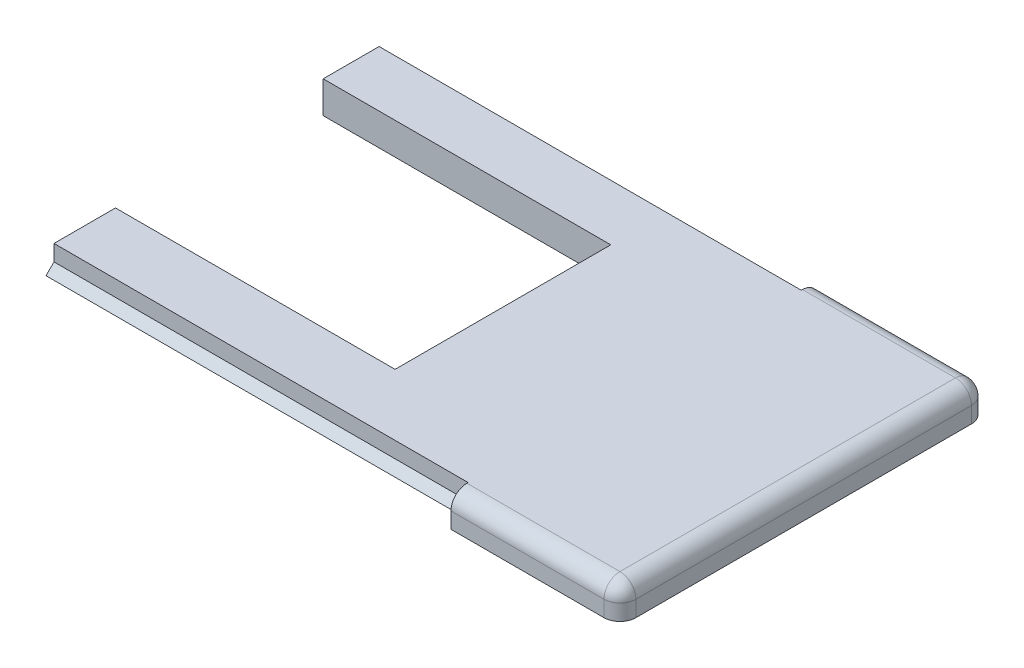
SolidWorks part; units mm, degrees
ref_plane "前视基准面" through (0, 0, 0) normal (0, 0, 1) x (1, 0, 0)
ref_plane "上视基准面" through (0, 0, 0) normal (0, 1, 0) x (1, 0, 0)
ref_plane "右视基准面" through (0, 0, 0) normal (1, 0, 0) x (0, 0, -1)
sketch "草图1" plane through (0, 0, 0) normal (0, 1, 0) x (1, 0, 0)
  line L0 (-35, -21) -> (35, -21)
  line L1 (-35, -21) -> (-35, 21)
  line L2 (-35, 21) -> (35, 21)
  line L3 (35, -21) -> (35, 21)
  line L4 (-35, -21) -> (35, 21) construction
  line L5 (-35, 21) -> (35, -21) construction
  line L10 (35, -21) -> (31, -21)
  line L11 (35, -21) -> (35, -18)
  line L14 (35, 21) -> (31, 21)
  line L15 (35, 21) -> (35, 18)
  line L18 (-35, -21) -> (-23, -21)
  line L19 (-35, -21) -> (-35, -18)
  line L22 (-37, -23) -> (37, -23)
  line L23 (-37, -23) -> (-37, 23)
  line L24 (-37, 23) -> (37, 23)
  line L25 (37, -23) -> (37, 23)
  line L26 (-37, -23) -> (37, 23) construction
  line L27 (-37, 23) -> (37, -23) construction
  line L28 (-34.85, -20.85) -> (-34.85, 20.85)
  line L29 (37, 23) -> (17, 23)
  line L30 (37, 23) -> (37, -23)
  line L31 (37, -23) -> (17, -23)
  line L32 (17, 23) -> (17, -23)
  line L33 (-35, -21) -> (17, -21)
  line L34 (-35, -21) -> (-35, 21)
  line L35 (-35, 21) -> (17, 21)
  line L36 (17, -21) -> (17, 21)
  line L37 (-34.85, 20.85) -> (16.85, 20.85)
  line L39 (-34.85, -20.85) -> (16.85, -20.85)
  line L40 (16.85, 20.85) -> (17, 20.85)
  line L41 (16.85, -20.85) -> (17, -20.85)
  line L43 (16.85, -20.85) -> (16.85, 20.85) construction
  point P0 (0, 0)
  point P21 (0, 0)
  dimension "D1" = 46
  dimension "D2" = 74
  dimension "D3" = 42
  dimension "D4" = 70
  dimension "D5" = 46
  dimension "D6" = 20
  dimension "D7" = 0.15
extrude "凸台-拉伸2" add sketch "草图1" along normal blind 4 contours L39 L41 L36 L40 L37 L28 | L2 L32 L36 L0 L3 | L24 L32 L2 L3 L0 L22 L25
sketch "草图3" plane through (17, 0, 0) normal (-1, 0, 0) x (0, 0, 1)
  line L0 (20.85, 2) -> (21.85, 1)
  line L1 (20.85, 4) -> (20.85, 0) construction
  line L2 (21.85, 1) -> (20.85, 0)
  line L3 (20.85, 4) -> (20.85, 0) construction
  line L4 (20.85, 0) -> (20.85, 2)
  line L5 (20.85, 0) -> (23, 0) construction
  dimension "D1" = 45
  dimension "D2" = 45
  dimension "D3" = 1
sketch "草图4" plane through (17, 0, 0) normal (-1, 0, 0) x (0, 0, 1)
  line L0 (-20.85, 2) -> (-21.85, 1)
  line L1 (-20.85, 4) -> (-20.85, 0) construction
  line L2 (-21.85, 1) -> (-20.85, 0)
  line L3 (-20.85, 4) -> (-20.85, 0) construction
  line L4 (-20.85, 0) -> (-20.85, 2)
  line L5 (-23, 0) -> (-20.85, 0) construction
  dimension "D1" = 45
  dimension "D2" = 45
  dimension "D3" = 1
extrude "凸台-拉伸3" add sketch "草图4" along normal up to surface (51.85 mm away) up to face at (-34.85, 2, 0)
extrude "凸台-拉伸4" add sketch "草图3" along normal up to surface (51.85 mm away) up to face at (-34.85, 1.8333, -7.1167)
sketch "草图6" plane through (0, 4, 0) normal (0, 1, 0) x (1, 0, 0)
  line L1 (-34.85, 20.85) -> (-31.85, 20.85)
  line L2 (-34.85, 20.85) -> (-34.85, 13.85)
  line L3 (-34.85, 13.85) -> (-31.85, 13.85)
  line L4 (-31.85, 20.85) -> (-31.85, 13.85)
  line L5 (-34.85, 20.85) -> (0.15, 20.85)
  line L6 (-34.85, 20.85) -> (-34.85, -13.15)
  line L7 (-34.85, -13.15) -> (0.15, -13.15)
  line L8 (-34.85, -20.85) -> (17, -20.85)
  line L9 (17, -20.85) -> (17, -23)
  line L10 (17, -23) -> (37, -23)
  line L11 (37, -23) -> (37, 23)
  line L12 (37, 23) -> (17, 23)
  line L13 (17, 23) -> (17, 20.85)
  line L14 (17, 20.85) -> (-34.85, 20.85)
  line L15 (-34.85, 20.85) -> (-34.85, -20.85)
  line L16 (-34.85, -20.85) -> (17, -20.85)
  line L17 (17, -20.85) -> (17, -23)
  line L18 (17, -23) -> (37, -23)
  line L19 (37, -23) -> (37, 23)
  line L20 (37, 23) -> (17, 23)
  line L21 (17, 23) -> (17, 20.85)
  line L22 (17, 20.85) -> (-34.85, 20.85)
  line L23 (-34.85, 20.85) -> (-34.85, -20.85)
  line L24 (0.15, 20.85) -> (0.15, -13.15)
  line L25 (-31.85, 13.85) -> (0.15, 13.85)
  line L26 (-31.85, 13.85) -> (-31.85, -13.15)
  line L27 (-31.85, -13.15) -> (0.15, -13.15)
  line L28 (0.15, 13.85) -> (0.15, -13.15)
  point P2 (-34.85, 0)
  line M28 (-34.85, 20.85) -> (-34.85, -20.85)
  dimension "D2" = 7
  dimension "D3" = 3
  dimension "D4" = 34
  dimension "D5" = 35
  dimension "D1" = 0
extrude "切除-拉伸1" cut sketch "草图6" against normal up to surface (4 mm away) contours L25 L26 L7 L24 | L26 L3 L7 M28 up to face at (9.0375, 0, 0)
sketch "草图7" plane through (37, 0, 0) normal (1, 0, 0) x (0, 0, -1)
  line L8 (-23, 0) -> (23, 0)
  line L9 (23, 0) -> (23, 4)
  line L10 (23, 4) -> (-23, 4)
  line L11 (-23, 4) -> (-23, 0)
  line L12 (-23, 0) -> (23, 0)
  line L13 (23, 0) -> (23, 4)
  line L14 (23, 4) -> (-23, 4)
  line L15 (-23, 4) -> (-23, 0)
  dimension "D1" = 0
extrude "凸台-拉伸5" add sketch "草图7" along normal blind 1.15
sketch "草图10" plane through (0, 4, 0) normal (0, 1, 0) x (1, 0, 0)
  line L1 (38.15, 23) -> (35.15, 23)
  line L2 (38.15, 23) -> (38.15, -23)
  line L3 (38.15, -23) -> (35.15, -23)
  line L4 (35.15, 23) -> (35.15, -23)
  line L5 (17, -23) -> (38.15, -23) construction
  line L6 (38.15, 0) -> (35.15, 0)
  point P10 (36.65, 0)
  dimension "D1" = 46
  dimension "D2" = 3
ref_plane "基准面4" through (0, 0, 0) normal (0, 0, 1) x (1, 0, 0)
sketch "草图11" plane through (0, 0, 0) normal (0, 0, 1) x (1, 0, 0)
  line L0 (35.9, 4) -> (36.65, 3.25)
  line L1 (38.15, 4) -> (35.15, 4) construction
  line L2 (36.65, 3.25) -> (37.4, 4)
  line L3 (36.65, 3.25) -> (36.65, 4)
  line L4 (37.4, 4) -> (35.9, 4)
  line L5 (35.9, 4) -> (36.65, 4.75)
  line L6 (36.65, 4.75) -> (37.4, 4)
  dimension "D1" = 45
  dimension "D2" = 45
  dimension "D3" = 0.75
sketch "草图12" plane through (0, 0, 0) normal (0, 0, 1) x (1, 0, 0)
  line L4 (36.65, -0.75) -> (36.65, 0)
  line L5 (38.15, 0) -> (35.15, 0)
  line L6 (17, 0) -> (38.15, 0) construction
  line L7 (37.4, 0) -> (36.65, -0.75)
  line L8 (36.65, -0.75) -> (35.9, 0)
  point P0 (36.65, 0)
  dimension "D1" = 45
  dimension "D2" = 45
  dimension "D3" = 0.75
  dimension "D4" = 3
extrude "凸台-拉伸6" add sketch "草图12" along normal mid plane 10 contours L7 L5 L4 | L8 L4 L5
sketch "草图13" plane through (0, 4, 0) normal (0, 1, 0) x (1, 0, 0)
  line L8 (-34.85, -20.85) -> (17, -20.85)
  line L9 (17, -20.85) -> (17, -23)
  line L10 (17, -23) -> (38.15, -23)
  line L11 (38.15, -23) -> (38.15, 23)
  line L12 (38.15, 23) -> (17, 23)
  line L13 (17, 23) -> (17, 20.85)
  line L14 (17, 20.85) -> (-34.85, 20.85)
  line L15 (-34.85, 20.85) -> (-34.85, 13.85)
  line L16 (-34.85, -20.85) -> (17, -20.85)
  line L17 (17, -20.85) -> (17, -23)
  line L18 (17, -23) -> (38.15, -23)
  line L19 (38.15, -23) -> (38.15, 23)
  line L20 (38.15, 23) -> (17, 23)
  line L21 (17, 23) -> (17, 20.85)
  line L22 (17, 20.85) -> (-34.85, 20.85)
  line L23 (-34.85, 20.85) -> (-34.85, 13.85)
  line L28 (-34.85, 13.85) -> (0.15, 13.85)
  line L29 (-34.85, 13.85) -> (0.15, 13.85)
  line L30 (0.15, 13.85) -> (0.15, -13.15)
  line L31 (0.15, 13.85) -> (0.15, -13.15)
  line L32 (0.15, -13.15) -> (-34.85, -13.15)
  line L33 (0.15, -13.15) -> (-34.85, -13.15)
  line L34 (-34.85, -13.15) -> (-34.85, -20.85)
  line L35 (-34.85, -13.15) -> (-34.85, -20.85)
  dimension "D1" = 0
sketch "草图14" plane through (-34.85, 0, 0) normal (-1, 0, 0) x (0, 0, 1)
  line L6 (-13.85, 0) -> (-13.85, 4)
  line L7 (-13.85, 0) -> (-13.85, 4)
  line L8 (-20.85, 0) -> (-13.85, 0)
  line L9 (-13.85, 4) -> (-20.85, 4)
  line L10 (-13.85, 4) -> (-20.85, 4)
  line L13 (-20.85, 4) -> (-20.85, 2)
  line L14 (-20.85, 2) -> (-21.85, 1)
  line L15 (-21.85, 1) -> (-20.85, 0)
  line L16 (-20.85, 0) -> (-13.85, 0)
  line L21 (-20.85, 4) -> (-20.85, 2)
  line L22 (-20.85, 2) -> (-21.85, 1)
  line L23 (-21.85, 1) -> (-20.85, 0)
  dimension "D1" = 0
extrude "凸台-拉伸7" add sketch "草图14" along normal blind 1 contours L16 L7 L10 L21 L22 L23
fillet "圆角3" radius 2 5 edges at (27.575, 4, -23) (38.15, 4, 0) (27.575, 4, 23) (38.15, 2, 23) (38.15, 2, -23)
